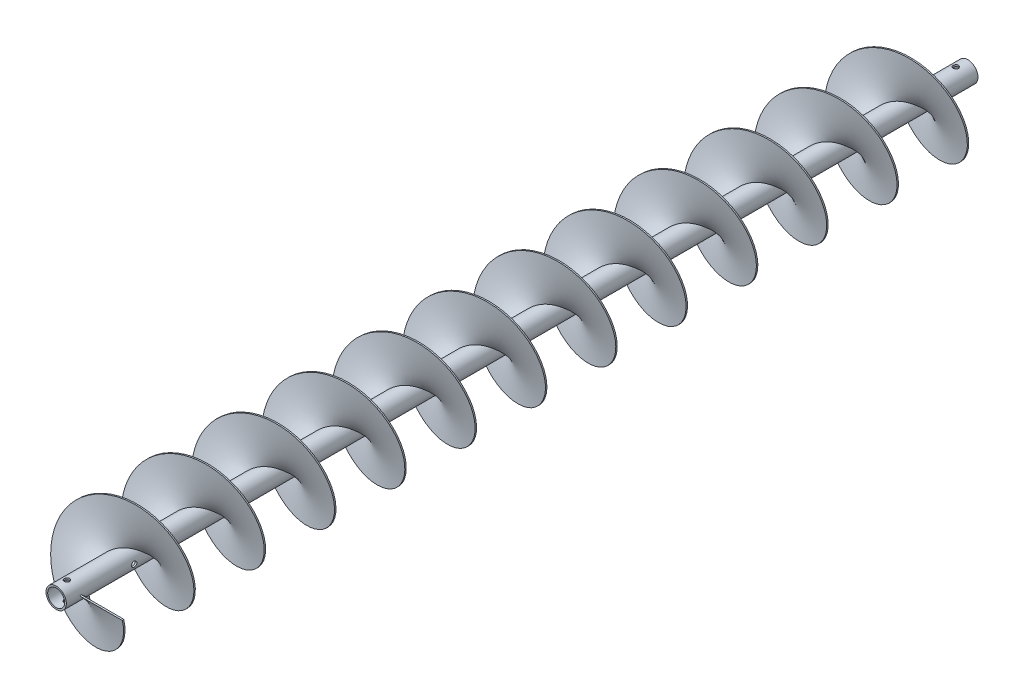
SolidWorks part; units mm, degrees
ref_plane "Front Plane" through (0, 0, 0) normal (0, 0, 1) x (1, 0, 0)
ref_plane "Top Plane" through (0, 0, 0) normal (0, 1, 0) x (1, 0, 0)
ref_plane "Right Plane" through (0, 0, 0) normal (1, 0, 0) x (0, 0, -1)
sketch "Sketch1" plane through (0, 0, 0) normal (0, 0, 1) x (1, 0, 0)
  circle A0 centre (0, 0) radius 21
  dimension "D1" = 42
extrude "Extrude-Thin1" add sketch "Sketch1" against normal blind 1880 thin thin type one direction reverse wall 3.5
ref_plane "Plane1" through (0, 0, -27.5) normal (0, 0, 1) x (1, 0, 0)
sketch "Sketch2" plane through (0, 0, -27.5) normal (0, 0, 1) x (1, 0, 0)
  circle A0 centre (0, 0) radius 65
  dimension "D1" = 130
curve "Helix/Spiral2" pitch 145 height 1800 turns 12.4138
ref_plane "Plane5" through (65, 0, -27.5) normal (0, -0.9424, -0.3346) x (-1, 0, 0)
sketch "Sketch7" plane through (65, 0, -27.5) normal (0, -0.9424, -0.3346) x (-1, 0, 0)
  line L0 (44, 1745.7378) -> (44, -25.9151) construction
  line L1 (-44, 0.0844) -> (44, 0.0844)
  line L2 (-44, 0.0844) -> (-44, 3)
  line L3 (-44, 3) -> (44, 3)
  line L4 (44, 0.0844) -> (44, 3)
  line L5 (-44, 0.0844) -> (44, 3) construction
  line L6 (-44, 3) -> (44, 0.0844) construction
  point P4 (0, 1.5422)
  point P7 (-0.0143, 2.5641)
  dimension "D1" = 65
  dimension "D2" = 25.9995
  dimension "D3" = 27.4573
sweep "Sweep1" add profiles "Sketch7" path "Helix/Spiral2"
sketch "Sketch9" plane through (0, 0, 0) normal (1, 0, 0) x (0, 0, -1)
  line L0 (1880, -21) -> (1880, 21) construction
  line L1 (0, 21) -> (0, -21) construction
  circle A0 centre (140, 0) radius 5.5
  circle A1 centre (1790, 0) radius 5.5
  dimension "D3" = 11
  dimension "D4" = 11
  dimension "D1" = 90
  dimension "D2" = 140
extrude "Cut-Extrude1" cut sketch "Sketch9" against normal through all both and the other way through all
sketch "Sketch10" plane through (0, 0, 0) normal (0, 1, 0) x (1, 0, 0)
  line L0 (21, 1880) -> (-21, 1880) construction
  line L1 (-21, 0) -> (21, 0) construction
  circle A0 centre (0, 22) radius 5.5
  circle A1 centre (0, 1855) radius 5.5
  dimension "D1" = 11
  dimension "D2" = 11
  dimension "D3" = 25
  dimension "D4" = 22
extrude "Cut-Extrude2" cut sketch "Sketch10" against normal through all both and the other way through all
